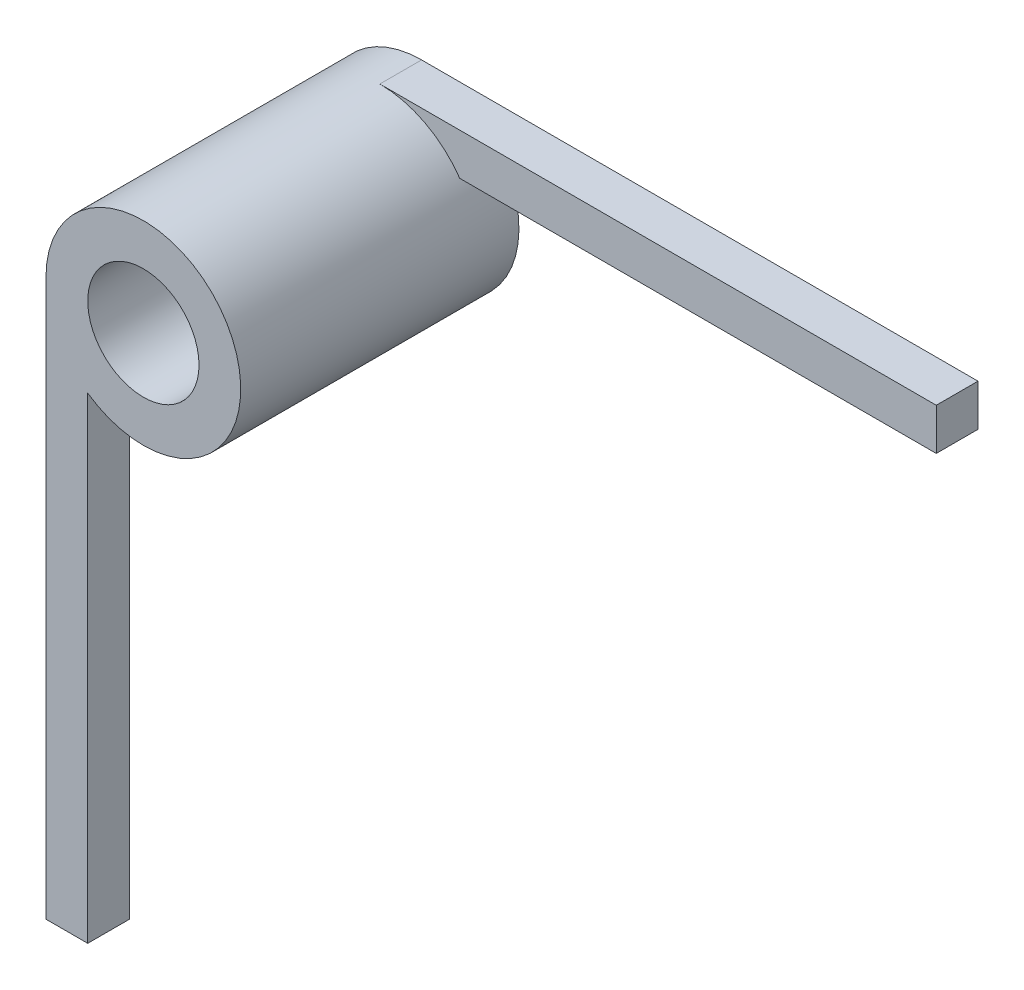
SolidWorks part; units mm, degrees
ref_plane "前视基准面" through (0, 0, 0) normal (0, 0, 1) x (1, 0, 0)
ref_plane "上视基准面" through (0, 0, 0) normal (0, 1, 0) x (1, 0, 0)
ref_plane "右视基准面" through (0, 0, 0) normal (1, 0, 0) x (0, 0, -1)
sketch "草图1" plane through (0, 0, 0) normal (0, 0, 1) x (1, 0, 0)
  circle A0 centre (0, 0) radius 1.75
  circle A1 centre (0, 0) radius 1
  dimension "D1" = 3.5
  dimension "D2" = 2
extrude "凸台-拉伸1" add sketch "草图1" along normal mid plane 5
sketch "草图3" plane through (0, 0, 2.5) normal (0, 0, 1) x (1, 0, 0)
  line L0 (-1.75, 0) -> (-1.75, -10)
  line L1 (-1.75, -10) -> (-1, -10)
  line L2 (-1, -10) -> (-1, 0)
  line L3 (-1.75, 0) -> (-1, 0)
  circle A0 centre (0, 0) radius 1.75 construction
  circle A1 centre (0, 0) radius 1 construction
  point P8 (-1.7497, 0.0301)
  dimension "D1" = 10
extrude "凸台-拉伸2" add sketch "草图3" against normal blind 0.75
sketch "草图4" plane through (0, 0, -2.5) normal (0, 0, -1) x (-1, 0, 0)
  line L0 (0, 1.75) -> (-10, 1.75)
  line L1 (-10, 1.75) -> (-10, 1)
  line L2 (-10, 1) -> (0, 1)
  line L3 (0, 1) -> (0, 1.75)
  circle A0 centre (0, 0) radius 1.75 construction
  circle A1 centre (0, 0) radius 1 construction
  dimension "D1" = 10
extrude "凸台-拉伸3" add sketch "草图4" against normal blind 0.75
